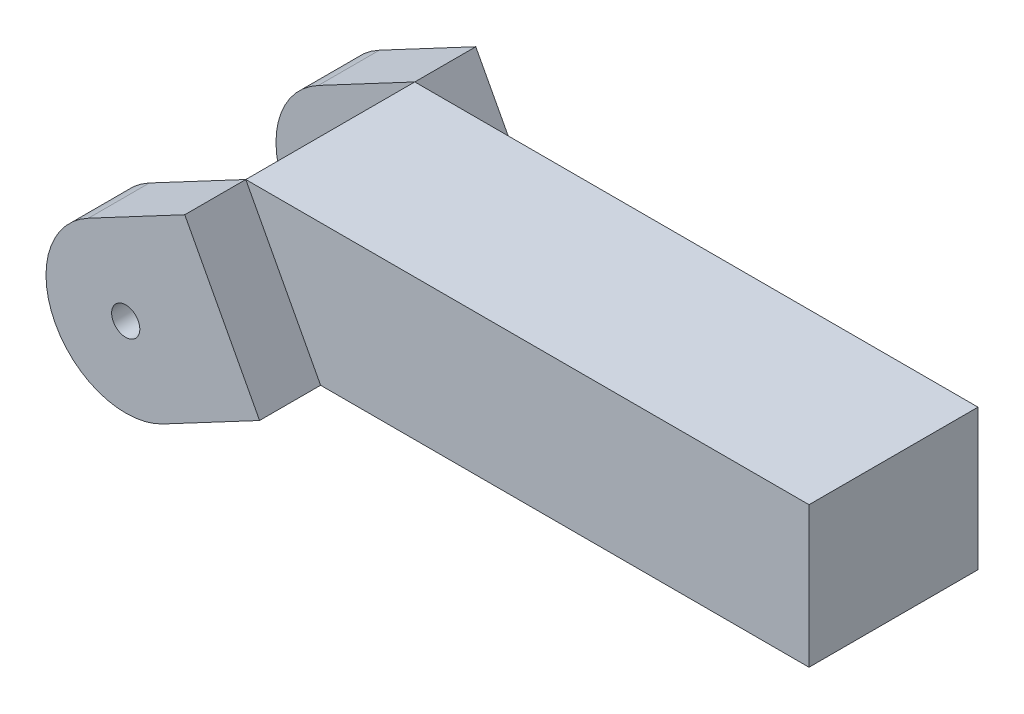
SolidWorks part; units mm, degrees
ref_plane "前视基准面" through (0, 0, 0) normal (0, 0, 1) x (1, 0, 0)
ref_plane "上视基准面" through (0, 0, 0) normal (0, 1, 0) x (1, 0, 0)
ref_plane "右视基准面" through (0, 0, 0) normal (1, 0, 0) x (0, 0, -1)
sketch "草图1" plane through (0, 0, 0) normal (0, 0, 1) x (1, 0, 0)
  line L1 (-60, 15) -> (60, 15)
  line L2 (-60, 15) -> (-60, -15)
  line L3 (-60, -15) -> (60, -15)
  line L4 (60, 15) -> (60, -15)
  line L5 (-60, 15) -> (60, -15) construction
  line L6 (-60, -15) -> (60, 15) construction
  point P0 (0, 0)
  dimension "D1" = 30
  dimension "D2" = 120
extrude "凸台-拉伸1" add sketch "草图1" along normal blind 36
sketch "草图2" plane through (0, 0, 0) normal (0, 0, -1) x (-1, 0, 0)
  line L0 (-60, 15) -> (60, 15) construction
  line L1 (-55, 10) -> (-14, 10)
  line L2 (-55, 10) -> (-55, -11)
  line L3 (-55, -11) -> (-14, -11)
  line L4 (-14, 10) -> (-14, -11)
  line L5 (-60, -15) -> (-60, 15) construction
  dimension "D1" = 5
  dimension "D2" = 5
  dimension "D3" = 41
  dimension "D4" = 21
extrude "切除-拉伸1" cut sketch "草图2" against normal blind 30 contours L1 L4 L3 L2
sketch "草图3" plane through (0, 0, 0) normal (0, 0, -1) x (-1, 0, 0)
  line L0 (-83.9789, 0) -> (77.6219, 0) construction
ref_plane "基准面1" through (0, 0, -13) normal (0, 0, -1) x (-1, 0, 0)
sketch "草图4" plane through (0, 0, -13) normal (0, 0, -1) x (-1, 0, 0)
  line L0 (60, 15) -> (44.0635, -15)
  line L1 (60, 15) -> (80.549, 4.0841)
  line L2 (44.0635, -15) -> (64.6125, -25.9159)
  line L4 (60, 15) -> (60, -15) construction
  line L5 (-60, 15) -> (60, 15) construction
  arc A0 (64.6125, -25.9159) -> (80.549, 4.0841) centre (72.5807, -10.9159) ccw
  circle A1 centre (72.5807, -10.9159) radius 3
  dimension "D1" = 6
extrude "凸台-拉伸2" add sketch "草图4" against normal up to surface (49 mm away)
ref_plane "基准面2" through (0, 0, 18) normal (0, 0, -1) x (-1, 0, 0)
mirror "镜向5" about plane through (0, 0, 18) normal (0, 0, -1) of bodies 112
sketch "草图6" plane through (-3.4832, 6.557, 0) normal (0.4691, -0.8831, 0) x (0.8831, 0.4691, 0)
  line L1 (-45.9507, 0) -> (-69.2191, 0)
  line L2 (-45.9507, 0) -> (-45.9507, 36)
  line L3 (-45.9507, 36) -> (-69.2191, 36)
  line L4 (-69.2191, 0) -> (-69.2191, 36)
extrude "切除-拉伸2" cut sketch "草图6" against normal through all
